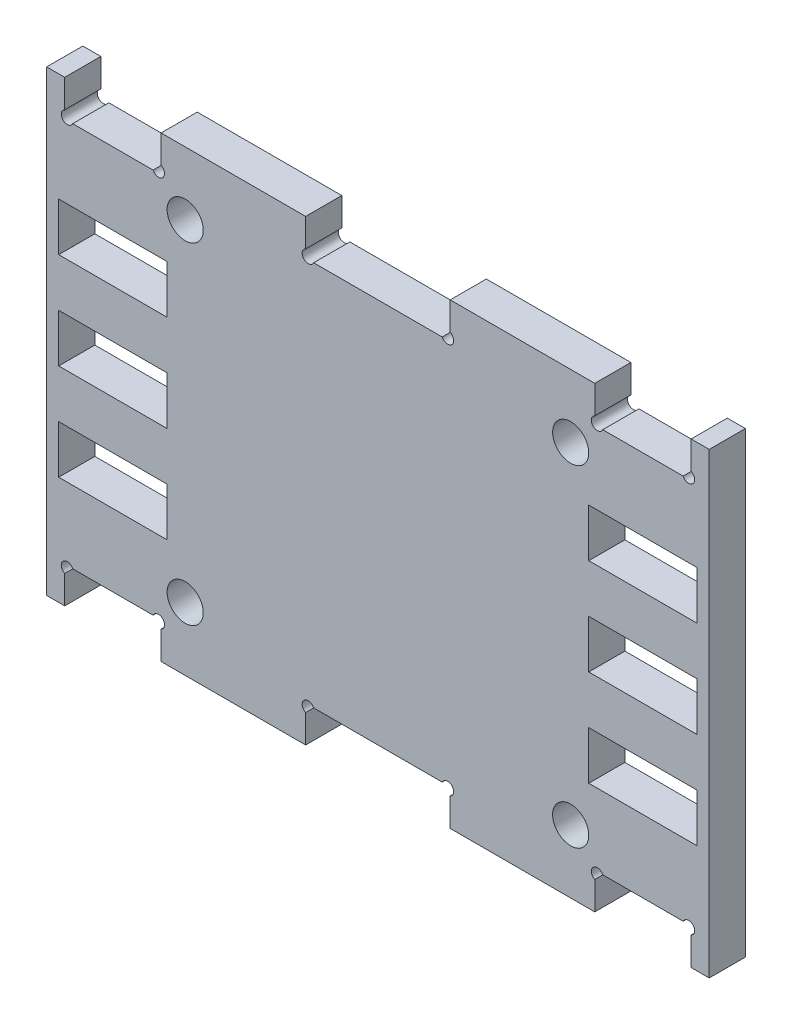
SolidWorks part; units mm, degrees
ref_plane "前视基准面" through (0, 0, 0) normal (0, 0, 1) x (1, 0, 0)
ref_plane "上视基准面" through (0, 0, 0) normal (0, 1, 0) x (1, 0, 0)
ref_plane "右视基准面" through (0, 0, 0) normal (1, 0, 0) x (0, 0, -1)
sketch "草图1" plane through (0, 0, 0) normal (0, 0, 1) x (1, 0, 0)
  line L1 (-27.5, 19) -> (27.5, 19)
  line L2 (-27.5, 19) -> (-27.5, -19)
  line L3 (-27.5, -19) -> (27.5, -19)
  line L4 (27.5, 19) -> (27.5, -19)
  line L5 (-27.5, 19) -> (27.5, -19) construction
  line L6 (-27.5, -19) -> (27.5, 19) construction
  point P0 (0, 0)
  dimension "D1" = 38
  dimension "D2" = 55
extrude "凸台-拉伸1" add sketch "草图1" along normal blind 3
sketch "草图2" plane through (0, 0, 3) normal (0, 0, 1) x (1, 0, 0)
  line L0 (-34.5256, 0) -> (42.1415, 0) construction
  line L1 (-10, -19) -> (-10, 19) construction
  line L2 (-27.5, -19) -> (27.5, -19) construction
  line L3 (27.5, 19) -> (-27.5, 19) construction
  line L4 (0, 26.7268) -> (0, -34.771) construction
  line L5 (10, -19) -> (10, 19) construction
  circle A0 centre (16, 13.75) radius 1.5
  circle A1 centre (16, -13.75) radius 1.5
  circle A2 centre (-16, 13.75) radius 1.5
  circle A3 centre (-16, -13.75) radius 1.5
  dimension "D1" = 13.75
  dimension "D2" = 3
  dimension "D3" = 10
  dimension "D4" = 6
extrude "切除-拉伸1" cut sketch "草图2" against normal blind 30
sketch "草图3" plane through (0, 0, 3) normal (0, 0, 1) x (1, 0, 0)
  line L0 (10, -19) -> (10, 19) construction
  line L1 (0, 26.7268) -> (0, -34.771) construction
  line L2 (-34.5256, 0) -> (42.1415, 0) construction
  line L3 (-10, -19) -> (-10, 19) construction
  line L4 (10, -19) -> (10, 19) construction
  line L5 (0, 26.7268) -> (0, -34.771) construction
  line L6 (-34.5256, 0) -> (42.1415, 0) construction
  line L7 (-10, -19) -> (-10, 19) construction
  line L8 (27.5, 19) -> (-27.5, 19) construction
  line L9 (27.5, -19) -> (27.5, 19) construction
  line L12 (18, 19) -> (26, 19)
  line L13 (18, 19) -> (18, 16)
  line L14 (18, 16) -> (26, 16)
  line L15 (26, 19) -> (26, 16)
  line L17 (26, -19) -> (26, -16)
  line L18 (18, -16) -> (26, -16)
  line L19 (18, -19) -> (18, -16)
  line L20 (18, -19) -> (26, -19)
  line L21 (-26, 19) -> (-26, 16)
  line L22 (-18, 16) -> (-26, 16)
  line L23 (-18, 19) -> (-18, 16)
  line L24 (-18, 19) -> (-26, 19)
  line L25 (-18, -19) -> (-26, -19)
  line L26 (-18, -19) -> (-18, -16)
  line L27 (-18, -16) -> (-26, -16)
  line L28 (-26, -19) -> (-26, -16)
  circle A0 centre (16, 13.75) radius 4 construction
  dimension "D1" = 8
  dimension "D2" = 1.5
  dimension "D3" = 8
  dimension "D4" = 3
extrude "切除-拉伸2" cut sketch "草图3" against normal blind 30
sketch "草图4" plane through (0, 0, 3) normal (0, 0, 1) x (1, 0, 0)
  line L0 (10, -19) -> (10, 19) construction
  line L1 (-10, -19) -> (-10, 19) construction
  line L2 (10, -19) -> (10, 19)
  line L3 (-10, -19) -> (-10, 19)
  line L4 (-10, -19) -> (10, -19)
  line L5 (-10, 19) -> (10, 19)
extrude "切除-拉伸3" [suppressed] cut sketch "草图4" against normal blind 1
sketch "草图5" plane through (0, 0, 3) normal (0, 0, 1) x (1, 0, 0)
  line L0 (-18, -19) -> (18, -19) construction
  line L1 (6, -19) -> (-6, -19)
  line L2 (6, -19) -> (6, -16)
  line L3 (6, -16) -> (-6, -16)
  line L4 (-6, -19) -> (-6, -16)
  line L5 (6, -19) -> (-6, -16) construction
  line L6 (6, -16) -> (-6, -19) construction
  line L7 (34.427, 0) -> (-42.806, 0) construction
  line L8 (6, 16) -> (-6, 19) construction
  line L9 (6, 19) -> (-6, 16) construction
  line L10 (-6, 19) -> (-6, 16)
  line L11 (6, 16) -> (-6, 16)
  line L12 (6, 19) -> (6, 16)
  line L13 (6, 19) -> (-6, 19)
  point P0 (0, -17.5)
  point P14 (0, 17.5)
  dimension "D1" = 3
  dimension "D2" = 12
extrude "切除-拉伸4" cut sketch "草图5" against normal blind 10
sketch "草图6" plane through (0, 0, 0) normal (0, 0, -1) x (-1, 0, 0)
  line L0 (-17.5, -6) -> (-17.5, -10) construction
  line L1 (-17.5, -10) -> (-26.5, -10) construction
  line L2 (-26.5, -10) -> (-26.5, -6) construction
  line L3 (-26.5, -6) -> (-17.5, -6) construction
  line L4 (-17.5, 2) -> (-17.5, -2) construction
  line L5 (-17.5, -2) -> (-26.5, -2) construction
  line L6 (-26.5, -2) -> (-26.5, 2) construction
  line L7 (-26.5, 2) -> (-17.5, 2) construction
  line L8 (-17.5, 10) -> (-17.5, 6) construction
  line L9 (-17.5, 6) -> (-26.5, 6) construction
  line L10 (-26.5, 6) -> (-26.5, 10) construction
  line L11 (-26.5, 10) -> (-17.5, 10) construction
  line L12 (26.5, -6) -> (26.5, -10) construction
  line L13 (26.5, -10) -> (17.5, -10) construction
  line L14 (17.5, -10) -> (17.5, -6) construction
  line L15 (17.5, -6) -> (26.5, -6) construction
  line L16 (26.5, 2) -> (26.5, -2) construction
  line L17 (26.5, -2) -> (17.5, -2) construction
  line L18 (17.5, -2) -> (17.5, 2) construction
  line L19 (17.5, 2) -> (26.5, 2) construction
  line L20 (17.5, 6) -> (17.5, 10) construction
  line L21 (26.5, 6) -> (17.5, 6) construction
  line L22 (26.5, 10) -> (26.5, 6) construction
  line L23 (17.5, 10) -> (26.5, 10) construction
  line L24 (-17.5, -6) -> (-17.5, -10)
  line L25 (-17.5, -10) -> (-26.5, -10)
  line L26 (-26.5, -10) -> (-26.5, -6)
  line L27 (-26.5, -6) -> (-17.5, -6)
  line L28 (-17.5, 2) -> (-17.5, -2)
  line L29 (-17.5, -2) -> (-26.5, -2)
  line L30 (-26.5, -2) -> (-26.5, 2)
  line L31 (-26.5, 2) -> (-17.5, 2)
  line L32 (-17.5, 10) -> (-17.5, 6)
  line L33 (-17.5, 6) -> (-26.5, 6)
  line L34 (-26.5, 6) -> (-26.5, 10)
  line L35 (-26.5, 10) -> (-17.5, 10)
  line L36 (26.5, -6) -> (26.5, -10)
  line L37 (26.5, -10) -> (17.5, -10)
  line L38 (17.5, -10) -> (17.5, -6)
  line L39 (17.5, -6) -> (26.5, -6)
  line L40 (26.5, 2) -> (26.5, -2)
  line L41 (26.5, -2) -> (17.5, -2)
  line L42 (17.5, -2) -> (17.5, 2)
  line L43 (17.5, 2) -> (26.5, 2)
  line L44 (17.5, 6) -> (17.5, 10)
  line L45 (26.5, 6) -> (17.5, 6)
  line L46 (26.5, 10) -> (26.5, 6)
  line L47 (17.5, 10) -> (26.5, 10)
extrude "切除-拉伸5" cut sketch "草图6" against normal blind 10
sketch "草图7" plane through (0, 0, 0) normal (0, 0, -1) x (-1, 0, 0)
  circle A1 centre (-18.2121, -16.2121) radius 0.5
  circle A2 centre (-18.2121, -16.2121) radius 0.5
  circle A3 centre (-25.7879, -16.2121) radius 0.5
  circle A4 centre (-25.7879, -16.2121) radius 0.5
  circle A5 centre (-25.7879, 16.2121) radius 0.5
  circle A6 centre (-25.7879, 16.2121) radius 0.5
  circle A7 centre (-18.2121, 16.2121) radius 0.5
  circle A8 centre (-18.2121, 16.2121) radius 0.5
  circle A9 centre (-5.7879, -16.2121) radius 0.5
  circle A10 centre (-5.7879, -16.2121) radius 0.5
  circle A11 centre (25.7879, -16.2121) radius 0.5
  circle A12 centre (25.7879, -16.2121) radius 0.5
  circle A13 centre (18.2121, -16.2121) radius 0.5
  circle A14 centre (18.2121, -16.2121) radius 0.5
  circle A15 centre (18.2121, 16.2121) radius 0.5
  circle A16 centre (18.2121, 16.2121) radius 0.5
  circle A17 centre (25.7879, 16.2121) radius 0.5
  circle A18 centre (25.7879, 16.2121) radius 0.5
  circle A19 centre (-5.7879, 16.2121) radius 0.5
  circle A20 centre (-5.7879, 16.2121) radius 0.5
  circle A21 centre (5.7879, 16.2121) radius 0.5
  circle A22 centre (5.7879, 16.2121) radius 0.5
  circle A23 centre (5.7879, -16.2121) radius 0.5
  circle A24 centre (5.7879, -16.2121) radius 0.5
  dimension "D1" = 0
  dimension "D2" = 0
  dimension "D3" = 0
  dimension "D4" = 0
  dimension "D5" = 0
  dimension "D6" = 0
  dimension "D7" = 0
  dimension "D8" = 0
  dimension "D9" = 0
  dimension "D10" = 0
  dimension "D11" = 0
  dimension "D12" = 0
extrude "切除-拉伸6" cut sketch "草图7" against normal blind 10
